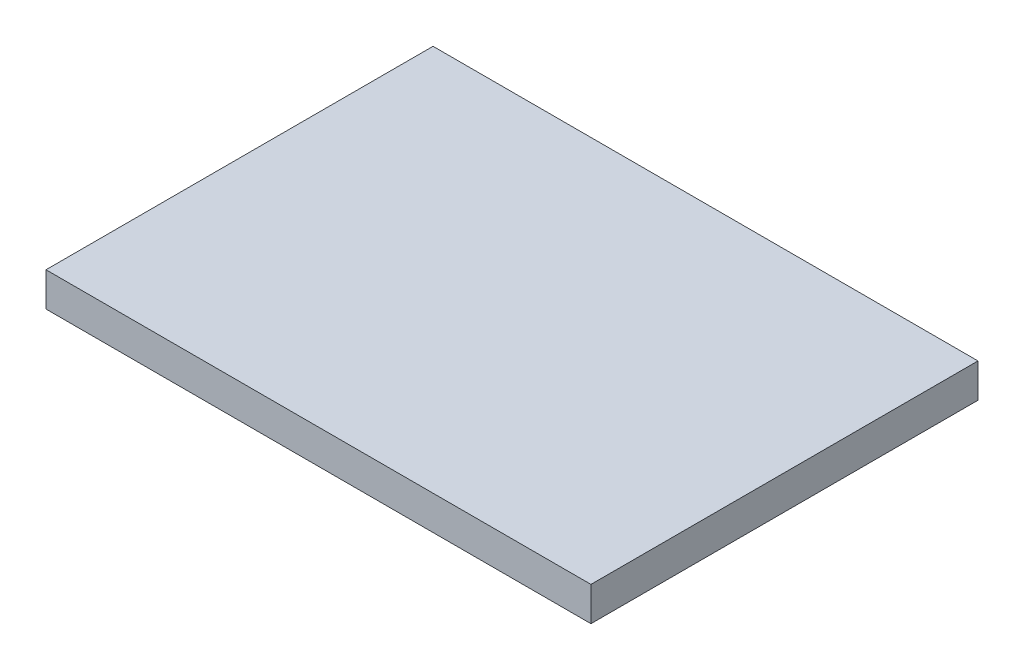
SolidWorks part; units mm, degrees
material "Glass"
ref_plane "Front Plane" through (0, 0, 0) normal (0, 0, 1) x (1, 0, 0)
ref_plane "Top Plane" through (0, 0, 0) normal (0, 1, 0) x (1, 0, 0)
ref_plane "Right Plane" through (0, 0, 0) normal (1, 0, 0) x (0, 0, -1)
sketch "Sketch1" plane through (0, 0, 0) normal (0, 1, 0) x (1, 0, 0)
  line L1 (-8.8, -6.25) -> (8.8, -6.25)
  line L2 (-8.8, -6.25) -> (-8.8, 6.25)
  line L3 (-8.8, 6.25) -> (8.8, 6.25)
  line L4 (8.8, -6.25) -> (8.8, 6.25)
  line L5 (-8.8, -6.25) -> (8.8, 6.25) construction
  line L6 (-8.8, 6.25) -> (8.8, -6.25) construction
  point P0 (0, 0)
  dimension "D1" = 17.6
  dimension "D2" = 12.5
extrude "Boss-Extrude1" add sketch "Sketch1" along normal blind 1.1
